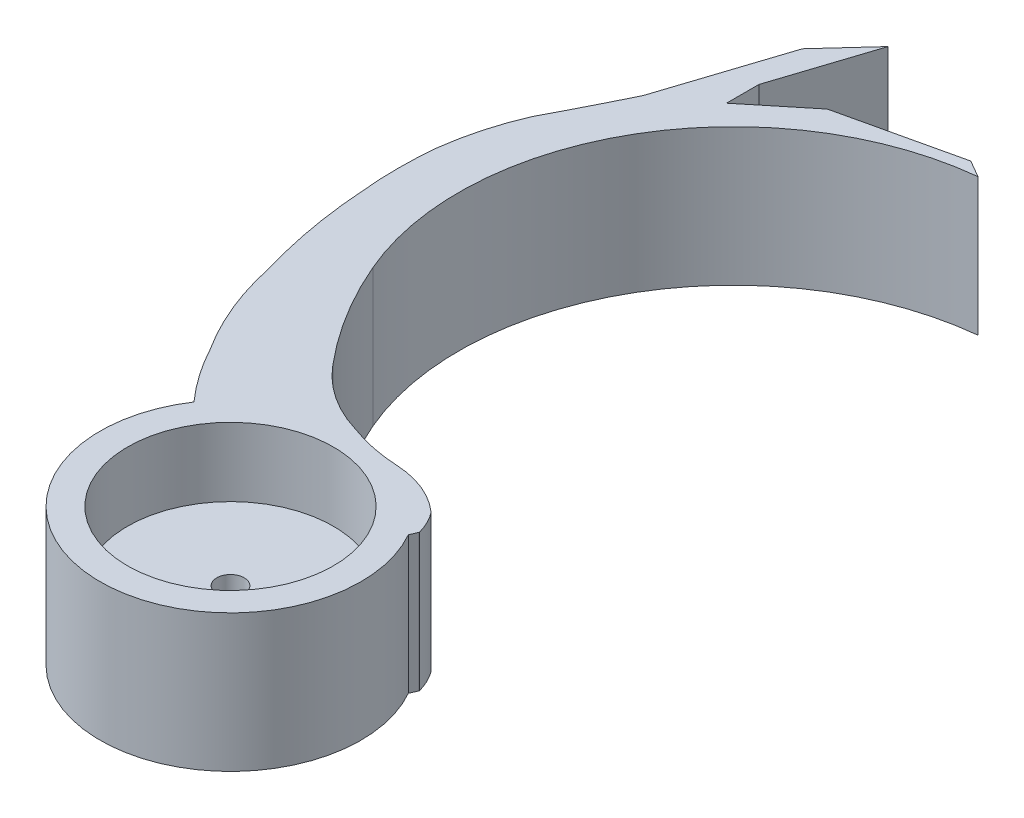
SolidWorks part; units mm, degrees
ref_plane "Front Plane" through (0, 0, 0) normal (0, 0, 1) x (1, 0, 0)
ref_plane "Top Plane" through (0, 0, 0) normal (0, 1, 0) x (1, 0, 0)
ref_plane "Right Plane" through (0, 0, 0) normal (1, 0, 0) x (0, 0, -1)
sketch "Sketch2" plane through (0, 0, 0) normal (0, 1, 0) x (1, 0, 0)
  line L0 (0, 0) -> (-35.9464, 0) construction
  line L1 (-35.9464, 0) -> (41.3976, 0) construction
  line L2 (41.3976, 0) -> (0, 0) construction
  line L3 (0, 0) -> (0, 18.7982) construction
  line L4 (0, 18.7982) -> (0, -23.465) construction
  circle A0 centre (0, 0) radius 20 construction
  circle A1 centre (0, 0) radius 23.465
sketch "Sketch4" plane through (0, 0, 0) normal (0, 1, 0) x (1, 0, 0)
  line L0 (-19.7005, -1.3216) -> (20.2972, -0.8891) construction
  circle A0 centre (0, 0) radius 23.4639 construction
  dimension "D1" = 40
sketch "Sketch5" plane through (0, 0, 0) normal (0, 1, 0) x (1, 0, 0)
  line L0 (-19.9303, -0.0851) -> (20.0695, 0.0365) construction
  dimension "D1" = 40
sketch "Sketch6" plane through (0, 0, 0) normal (0, 1, 0) x (1, 0, 0)
  circle A0 centre (-4.3374, 0.8589) radius 20
sketch "sungu kiri " plane through (0, 0, 0) normal (0, 1, 0) x (1, 0, 0)
  line L0 (-17.9037, 25.6768) -> (-20.2142, 18.582)
  line L1 (-20.2142, 18.582) -> (-20.2142, 16.2232)
  line L2 (-16.1729, 19.5215) -> (-7.6679, 21.4704)
  line L3 (-3.7576, -22.025) -> (-3.6458, -22.025)
  line L4 (-17.9037, 25.6768) -> (-20.8793, 22.4196)
  line L5 (-20.8793, 22.4196) -> (-23.726, 13.6785)
  line L6 (-23.3814, 7.2187) -> (-21.0655, 13.8643)
  line L8 (-21.0655, 13.8643) -> (-20.2142, 18.582)
  line L9 (-7.6679, 21.4704) -> (-6.4236, 20.7498)
  line L10 (-4.3374, 0.8589) -> (-4.3374, 13.8643) construction
  line L11 (7.4981, 19.5215) -> (11.5395, 16.2232)
  line L14 (-16.1729, 19.5215) -> (-20.2142, 16.2232)
  line L15 (-1.0069, 21.4704) -> (-2.2512, 20.7498)
  line L16 (12.3908, 13.8643) -> (11.5395, 18.582)
  line L17 (14.7066, 7.2187) -> (12.3908, 13.8643)
  line L18 (12.2046, 22.4196) -> (15.0512, 13.6785)
  line L19 (9.2289, 25.6768) -> (12.2046, 22.4196)
  line L21 (7.4981, 19.5215) -> (-1.0069, 21.4704)
  line L22 (11.5395, 18.582) -> (11.5395, 16.2232)
  line L23 (9.2289, 25.6768) -> (11.5395, 18.582)
  line L24 (-4.3374, 0.8589) -> (-4.3374, -17.8442) construction
  arc A0 (-4.3374, -21.9985) -> (-5.1555, -20.3392) centre (-9.0425, -23.287) ccw
  arc A1 (-5.1555, -20.3392) -> (-9.3619, -18.6184) centre (-9.6898, -25.4217) ccw
  arc A2 (-9.3619, -18.6184) -> (-13.1502, -17.8442) centre (-8.7528, -5.9825) cw
  arc A3 (-13.1502, -17.8442) -> (-18.7296, -13.6646) centre (-10.3234, -8.257) cw
  arc A4 (-22.7226, -7.0141) -> (-17.1413, 16.2232) centre (-4.3374, 0.8589) cw
  arc A5 (10.0549, -13.6646) -> (-4.1465, -21.4375) centre (-5.9719, -1.2427) cw construction
  arc A6 (8.4665, 16.2232) -> (-2.2512, 20.7498) centre (-4.3374, 0.8589) ccw
  arc A8 (-23.726, 13.6785) -> (-26.4444, 8.3095) centre (-176.3922, 87.6034) cw
  arc A9 (-26.4444, 8.3095) -> (-27.9369, 2.8451) centre (-7.9567, 0.3238) ccw
  arc A10 (-27.9369, 2.8451) -> (-27.9369, -2.4841) centre (-0.9166, 0.1805) ccw
  arc A11 (-27.9369, -2.4841) -> (-26.4444, -10.8627) centre (10.027, -0.0436) ccw
  arc A12 (-26.4444, -10.8627) -> (-23.4884, -18.0953) centre (-5.339, -6.4571) ccw
  arc A13 (-23.4884, -18.0953) -> (-19.0281, -23.7304) centre (-5.5688, -8.4944) ccw
  arc A14 (-19.0281, -23.7304) -> (-13.725, -28.6503) centre (23.0714, 16.3305) ccw
  arc A16 (-3.6458, -22.025) -> (-1.6826, -20.6262) centre (-3.6458, -19.9479) ccw
  arc A17 (9.1757, -14.8335) -> (14.0478, -7.0141) centre (-13.806, 4.9136) ccw
  arc A18 (-18.7296, -13.6646) -> (-5.4169, -21.3374) centre (-2.7028, -1.2427) ccw construction
  arc A19 (-17.8504, -14.8335) -> (-22.7226, -7.0141) centre (5.1312, 4.9136) cw
  circle A20 centre (-4.3374, 0.8589) radius 20 construction
  circle A21 centre (-12.8438, -27.2612) radius 9.5 construction
  arc A23 (-17.1413, 16.2232) -> (-6.4236, 20.7498) centre (-4.3374, 0.8589) cw
  arc A25 (10.3533, -23.7304) -> (5.0502, -28.6503) centre (-31.7461, 16.3305) cw
  arc A26 (14.8136, -18.0953) -> (10.3533, -23.7304) centre (-3.106, -8.4944) cw
  arc A27 (17.7696, -10.8627) -> (14.8136, -18.0953) centre (-3.3358, -6.4571) cw
  arc A28 (19.2622, -2.4841) -> (17.7696, -10.8627) centre (-18.7017, -0.0436) cw
  arc A29 (19.2622, 2.8451) -> (19.2622, -2.4841) centre (-7.7582, 0.1805) cw
  arc A30 (17.7696, 8.3095) -> (19.2622, 2.8451) centre (-0.7181, 0.3238) cw
  arc A31 (15.0512, 13.6785) -> (17.7696, 8.3095) centre (167.7174, 87.6034) ccw
  arc A32 (14.0478, -7.0141) -> (8.4665, 16.2232) centre (-4.3374, 0.8589) ccw
  arc A33 (4.4754, -17.8442) -> (10.0549, -13.6646) centre (1.6487, -8.257) ccw
  arc A34 (0.6871, -18.6184) -> (4.4754, -17.8442) centre (0.0781, -5.9825) ccw
  arc A35 (-3.5193, -20.3392) -> (0.6871, -18.6184) centre (1.015, -25.4217) cw
  arc A36 (-4.3446, -22.025) -> (-3.5193, -20.3392) centre (0.3678, -23.287) cw
  circle A37 centre (-12.8438, -27.2612) radius 7.5
  arc A38 (-8.788, -18.6705) -> (-4.5823, -22.5711) centre (-12.8438, -27.2612) ccw construction
  circle A39 centre (4.169, -27.2612) radius 7.5 construction
  circle A40 centre (4.169, -27.2612) radius 9.5 construction
  circle A41 centre (-12.8438, -27.2612) radius 1
  arc A42 (-13.725, -17.8021) -> (-4.5823, -22.5711) centre (-12.8438, -27.2612) ccw
  arc A43 (-4.3446, -22.025) -> (-4.5823, -22.5711) centre (-16.7026, -16.9703) cw
  arc A44 (-8.788, -18.6705) -> (-8.8094, -18.6604) centre (-12.8438, -27.2612) ccw
  dimension "D1" = 2
  dimension "D2" = 2
  dimension "D3" = 15
sketch "hjgjg" plane through (0, 0, 0) normal (0, 0, 1) x (1, 0, 0)
  line L0 (0, 0) -> (-35.9464, 0) construction
  line L1 (-35.9464, 0) -> (41.3976, 0) construction
  line L2 (41.3976, 0) -> (0, 0) construction
  line L3 (0, 0) -> (0, 18.7982) construction
  line L4 (0, 18.7982) -> (0, -23.465) construction
  circle A0 centre (0, 0) radius 20 construction
  circle A1 centre (0, 0) radius 23.465
extrude "Boss-Extrude1" add sketch "sungu kiri " along normal blind 10
sketch "Sketch7" plane through (0, 0, 0) normal (0, 1, 0) x (1, 0, 0)
  circle A0 centre (-12.8438, -27.2612) radius 7.5
sketch "Sketch9" plane through (0, 10, 0) normal (0, 1, 0) x (1, 0, 0)
  circle A0 centre (-12.8438, -27.2612) radius 7.5
extrude "Cut-Extrude5" cut sketch "Sketch9" against normal blind 5
